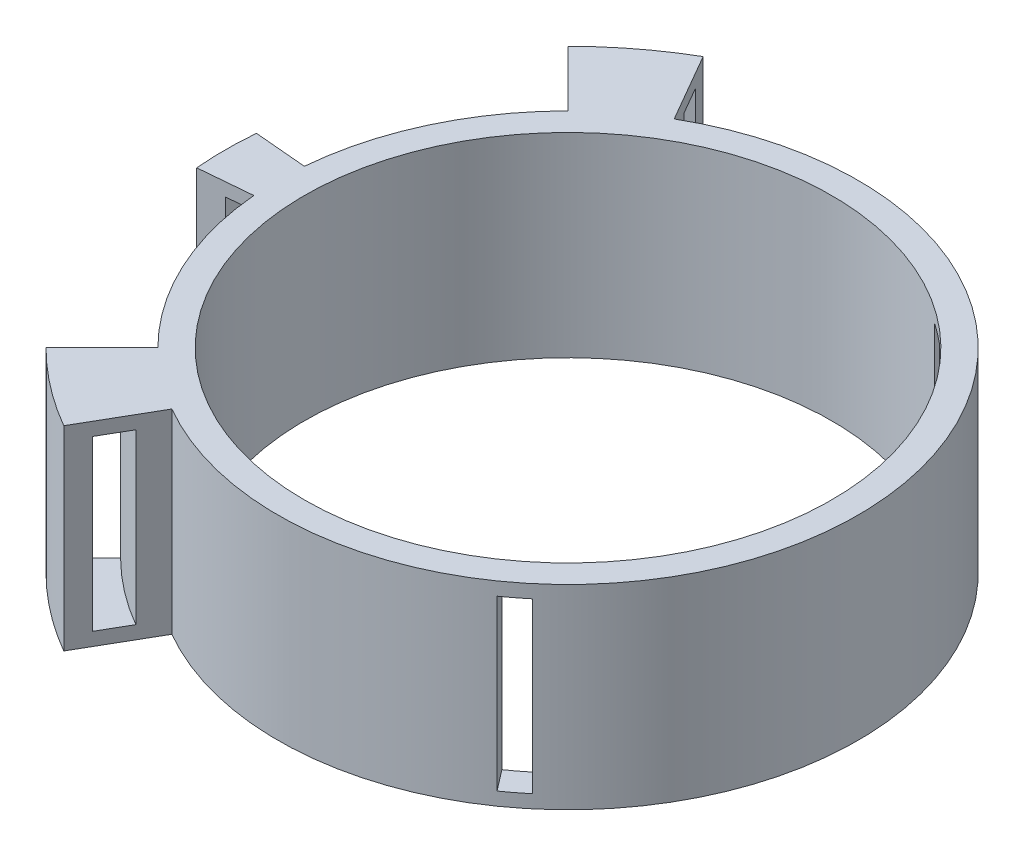
SolidWorks part; units mm, degrees
ref_plane "前视基准面" through (0, 0, 0) normal (0, 0, 1) x (1, 0, 0)
ref_plane "上视基准面" through (0, 0, 0) normal (0, 1, 0) x (1, 0, 0)
ref_plane "右视基准面" through (0, 0, 0) normal (1, 0, 0) x (0, 0, -1)
sketch "草图1" plane through (0, 0, 0) normal (0, 1, 0) x (1, 0, 0)
  line L0 (0, 0) -> (10.9581, -0.9587) construction
  line L1 (0, 0) -> (10.9581, 0.9587) construction
  line L2 (10.9581, 0.9587) -> (9.9619, 0.8716)
  line L3 (10.9581, -0.9587) -> (9.9619, -0.8716)
  line L5 (0, 0) -> (-5, -8.6603) construction
  line L6 (0, 0) -> (-7.0711, -7.0711) construction
  line L7 (0, 0) -> (-5, 8.6603) construction
  line L10 (0, 0) -> (-7.0711, 7.0711) construction
  line L11 (-7.7782, 7.7782) -> (-9.8995, 9.8995)
  line L12 (-5.5, 9.5263) -> (-7, 12.1244)
  line L13 (-7.7782, -7.7782) -> (-9.8995, -9.8995)
  line L14 (-5.5, -9.5263) -> (-7, -12.1244)
  line L15 (0, 0) -> (-14.5, 0) construction
  line L16 (0, 0) -> (-9.9619, 0.8716) construction
  line L17 (0, 0) -> (-9.9619, -0.8716) construction
  line L18 (-10.9581, 0.9587) -> (-12.9505, 1.133)
  line L19 (-10.9581, -0.9587) -> (-12.9505, -1.133)
  arc A0 (9.9619, 0.8716) -> (9.9619, -0.8716) centre (0, 0) ccw
  arc A1 (10.9581, 0.9587) -> (-5.5, 9.5263) centre (0, 0) ccw
  arc A2 (-7, 12.1244) -> (-9.8995, 9.8995) centre (0, 0) ccw
  arc A3 (-9.8995, -9.8995) -> (-7, -12.1244) centre (0, 0) ccw
  arc A4 (-7.7782, 7.7782) -> (-10.9581, 0.9587) centre (0, 0) ccw
  arc A5 (-5.5, -9.5263) -> (10.9581, -0.9587) centre (0, 0) ccw
  arc A6 (-12.9505, 1.133) -> (-12.9505, -1.133) centre (0, 0) ccw
  arc A7 (-10.9581, -0.9587) -> (-7.7782, -7.7782) centre (0, 0) ccw
extrude "凸台-拉伸1" add sketch "草图1" along normal blind 0.5
sketch "草图10" plane through (0, 0.5, 0) normal (0, 1, 0) x (1, 0, 0)
  line L0 (0, 0) -> (9.9619, -0.8716) construction
  line L1 (9.9619, -0.8716) -> (10.9581, -0.9587)
  line L2 (9.9619, 0.8716) -> (10.9581, 0.9587)
  line L3 (0, 0) -> (7.0707, -8.4265) construction
  line L4 (7.0707, -8.4265) -> (6.3145, -9.0071) construction
  line L5 (6.3145, -9.0071) -> (5.7049, -8.2131) construction
  line L6 (7.0707, -8.4265) -> (6.4279, -7.6604)
  line L7 (6.3145, -9.0071) -> (5.7049, -8.2131)
  line L8 (0, 0) -> (7.0287, 8.4615) construction
  line L9 (7.0287, 8.4615) -> (6.2688, 9.039) construction
  line L10 (6.2688, 9.039) -> (5.6631, 8.2419) construction
  line L11 (5.6631, 8.2419) -> (6.2688, 9.039)
  line L12 (7.0287, 8.4615) -> (6.3897, 7.6923)
  arc A0 (9.9619, 0.8716) -> (6.3897, 7.6923) centre (0, 0) ccw
  arc A1 (10.9581, 0.9587) -> (7.0287, 8.4615) centre (0, 0) ccw
  arc A2 (10.9581, 0.9587) -> (-5.5, 9.5263) centre (0, 0) ccw construction
  arc A3 (6.4279, -7.6604) -> (9.9619, -0.8716) centre (0, 0) ccw
  arc A4 (7.0707, -8.4265) -> (10.9581, -0.9587) centre (0, 0) ccw
  arc A5 (5.6631, 8.2419) -> (5.7049, -8.2131) centre (0, 0) ccw
  arc A6 (6.2688, 9.039) -> (6.3145, -9.0071) centre (0, 0) ccw
  arc M10 (10.9581, 0.9587) -> (-5.5, 9.5263) centre (0, 0) ccw
  line M11 (10.9581, -0.9587) -> (9.9619, -0.8716)
  arc M12 (9.9619, -0.8716) -> (9.9619, 0.8716) centre (0, 0) cw
  line M13 (9.9619, 0.8716) -> (10.9581, 0.9587)
extrude "凸台-拉伸2" add sketch "草图10" along normal blind 6.4 contours L6 M10 M11 M12 | L11 L7 M12 M10 | L12 M10 M12 M13
sketch "草图11" plane through (0, 6.9, 0) normal (0, 1, 0) x (1, 0, 0)
  line L0 (10.9581, -0.9587) -> (9.9619, -0.8716) construction
  line L1 (9.9619, 0.8716) -> (10.9581, 0.9587)
  line L2 (9.9619, -0.8716) -> (10.9581, -0.9587)
  arc A0 (9.9619, 0.8716) -> (9.9619, -0.8716) centre (0, 0) ccw
  arc A1 (10.9581, 0.9587) -> (10.9581, -0.9587) centre (0, 0) ccw
  arc A2 (7.0707, -8.4265) -> (10.9581, -0.9587) centre (0, 0) ccw construction
extrude "凸台-拉伸3" add sketch "草图11" along normal blind 0.5
sketch "草图12" plane through (0, 0.5, 0) normal (0, 1, 0) x (1, 0, 0)
  line L2 (0, 0) -> (-5.4967, 0) construction
  line L3 (-7.7782, -7.7782) -> (-8.4853, -8.4853)
  line L4 (-7.7782, -7.7782) -> (-9.8995, -9.8995) construction
  line L5 (-5.5, -9.5263) -> (-6, -10.3923)
  line L6 (-7, -12.1244) -> (-5.5, -9.5263) construction
  line L7 (-9.8995, -9.8995) -> (-9.3338, -9.3338)
  line L8 (-7, -12.1244) -> (-6.6, -11.4315)
  line L9 (-9.8995, 9.8995) -> (-9.3338, 9.3338)
  line L10 (-7, 12.1244) -> (-6.6, 11.4315)
  line L11 (-5.5, 9.5263) -> (-6, 10.3923)
  line L12 (-7.7782, 7.7782) -> (-8.4853, 8.4853)
  line L15 (-10.9581, 0.9587) -> (-12.9505, 1.133) construction
  line L17 (-12.9505, -1.133) -> (-10.9581, -0.9587) construction
  line L19 (-12.9505, 1.133) -> (-11.9543, 1.0459)
  line L20 (-12.9505, -1.133) -> (-11.9543, -1.0459)
  arc A0 (-9.8995, -9.8995) -> (-7, -12.1244) centre (0, 0) ccw
  arc A1 (-7.7782, -7.7782) -> (-5.5, -9.5263) centre (0, 0) ccw
  arc A2 (-8.4853, -8.4853) -> (-6, -10.3923) centre (0, 0) ccw
  arc A3 (-9.3338, -9.3338) -> (-6.6, -11.4315) centre (0, 0) ccw
  arc A4 (-9.8995, 9.8995) -> (-7, 12.1244) centre (0, 0) cw
  arc A5 (-9.3338, 9.3338) -> (-6.6, 11.4315) centre (0, 0) cw
  arc A6 (-7.7782, 7.7782) -> (-5.5, 9.5263) centre (0, 0) cw
  arc A7 (-8.4853, 8.4853) -> (-6, 10.3923) centre (0, 0) cw
  arc A10 (-11.9543, 1.0459) -> (-11.9543, -1.0459) centre (0, 0) ccw
  arc A12 (-12.9505, -1.133) -> (-12.9505, 1.133) centre (0, 0) cw
sketch "草图14" plane through (0, 7.4, 0) normal (0, 1, 0) x (1, 0, 0)
  line L0 (9.9619, 0.8716) -> (10.9581, 0.9587) construction
  line L1 (9.9619, 0.8716) -> (10.9581, 0.9587)
  line L2 (9.9619, -0.8716) -> (10.9581, -0.9587)
  arc A0 (9.9619, -0.8716) -> (9.9619, 0.8716) centre (0, 0) ccw
  arc A1 (10.9581, -0.9587) -> (10.9581, 0.9587) centre (0, 0) ccw
extrude "凸台-拉伸6" add sketch "草图14" against normal blind 7.4
extrude "凸台-拉伸7" add sketch "草图12" along normal blind 6.4
sketch "草图15" plane through (0, 6.9, 0) normal (0, 1, 0) x (1, 0, 0)
  line L2 (-12.9505, 1.133) -> (-10.9581, 0.9587)
  line L3 (-11.9543, 1.0459) -> (-12.9505, 1.133) construction
  line L4 (-12.9505, -1.133) -> (-10.9581, -0.9587)
  line L5 (-12.9505, -1.133) -> (-11.9543, -1.0459) construction
  line L6 (-9.8995, -9.8995) -> (-7.7782, -7.7782)
  line L7 (-7, -12.1244) -> (-5.5, -9.5263)
  line L8 (-9.8995, 9.8995) -> (-7.7782, 7.7782)
  line L9 (-7, 12.1244) -> (-5.5, 9.5263)
  arc A1 (-12.9505, -1.133) -> (-12.9505, 1.133) centre (0, 0) cw
  arc A2 (-10.9581, 0.9587) -> (-10.9581, -0.9587) centre (0, 0) ccw
  arc A3 (-7.7782, -7.7782) -> (-5.5, -9.5263) centre (0, 0) ccw
  arc A4 (-9.8995, -9.8995) -> (-7, -12.1244) centre (0, 0) ccw
  arc A5 (-7, 12.1244) -> (-9.8995, 9.8995) centre (0, 0) ccw
  arc A6 (-5.5, 9.5263) -> (-7.7782, 7.7782) centre (0, 0) ccw
extrude "凸台-拉伸8" add sketch "草图15" along normal blind 0.5
